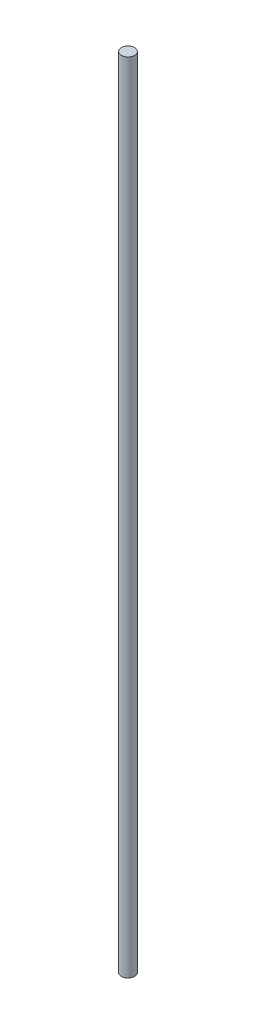
SolidWorks part; units mm, degrees
material "Hexcel AS4C (3000 Filaments)"
ref_plane "Front Plane" through (0, 0, 0) normal (0, 0, 1) x (1, 0, 0)
ref_plane "Top Plane" through (0, 0, 0) normal (0, 1, 0) x (1, 0, 0)
ref_plane "Right Plane" through (0, 0, 0) normal (1, 0, 0) x (0, 0, -1)
sketch "Sketch1" plane through (0, 0, 0) normal (0, 1, 0) x (1, 0, 0)
  circle A0 centre (0, 0) radius 1.016
  dimension "D1" = 2.032
extrude "Boss-Extrude1" add sketch "Sketch1" along normal blind 120.65
